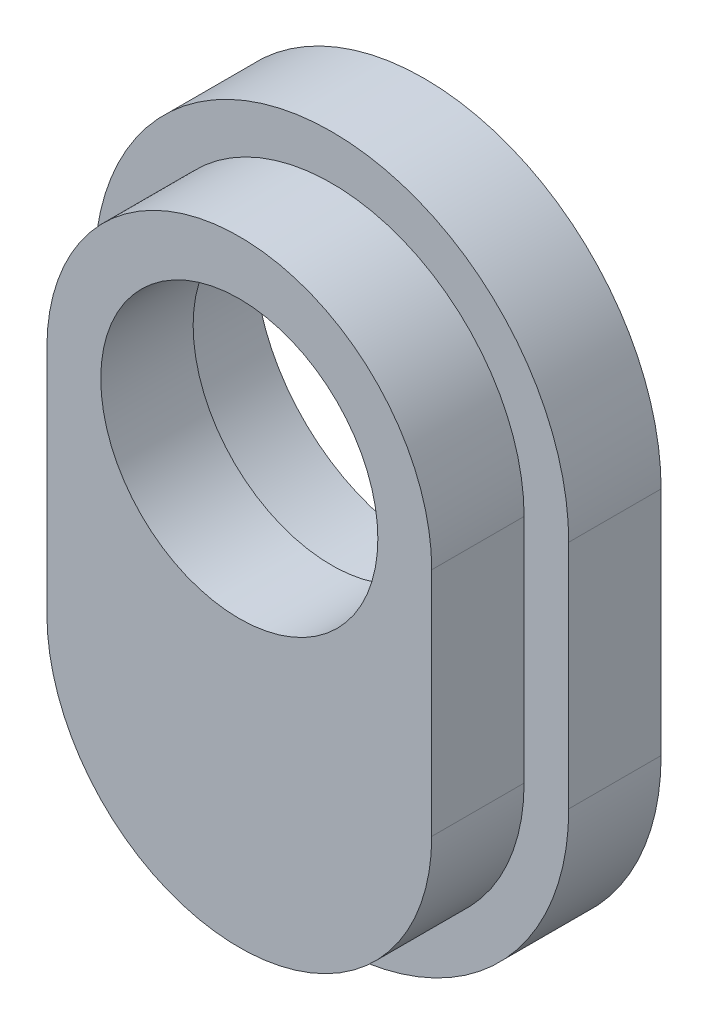
SolidWorks part; units mm, degrees
ref_plane "Front Plane" through (0, 0, 0) normal (0, 0, 1) x (1, 0, 0)
ref_plane "Top Plane" through (0, 0, 0) normal (0, 1, 0) x (1, 0, 0)
ref_plane "Right Plane" through (0, 0, 0) normal (1, 0, 0) x (0, 0, -1)
sketch "Sketch1" plane through (0, 0, 0) normal (0, 0, 1) x (1, 0, 0)
  line L0 (0, 0) -> (0, -7.5) construction
  line L1 (6.25, 0) -> (6.25, -7.5)
  line L2 (-6.25, 0) -> (-6.25, -7.5)
  arc A0 (6.25, 0) -> (-6.25, 0) centre (0, 0) ccw
  arc A1 (-6.25, -7.5) -> (6.25, -7.5) centre (0, -7.5) ccw
  circle A2 centre (0, 0) radius 4.5
  point P3 (0, -3.75)
  dimension "11" = 9
  dimension "D1" = 7.5
  dimension "D2" = 12.5
extrude "Boss-Extrude1" add sketch "Sketch1" along normal blind 6
sketch "Sketch3" plane through (0, 0, 0) normal (0, 0, -1) x (-1, 0, 0)
  line L0 (0, 0) -> (0, -7.5) construction
  line L1 (7.7, 0) -> (7.7, -7.5)
  line L2 (-7.7, 0) -> (-7.7, -7.5)
  arc A0 (7.7, 0) -> (-7.7, 0) centre (0, 0) ccw
  arc A1 (-7.7, -7.5) -> (7.7, -7.5) centre (0, -7.5) ccw
  circle A2 centre (0, 0) radius 5.5
  point P4 (0, -3.75)
  dimension "D2" = 11
  dimension "D1" = 15.4
extrude "Boss-Extrude2" add sketch "Sketch3" against normal blind 3
sketch "Sketch4" plane through (0, 0, 0) normal (0, 0, -1) x (-1, 0, 0)
  circle A0 centre (0, 0) radius 5.5
  dimension "D1" = 11
extrude "Cut-Extrude1" cut sketch "Sketch4" against normal blind 3
